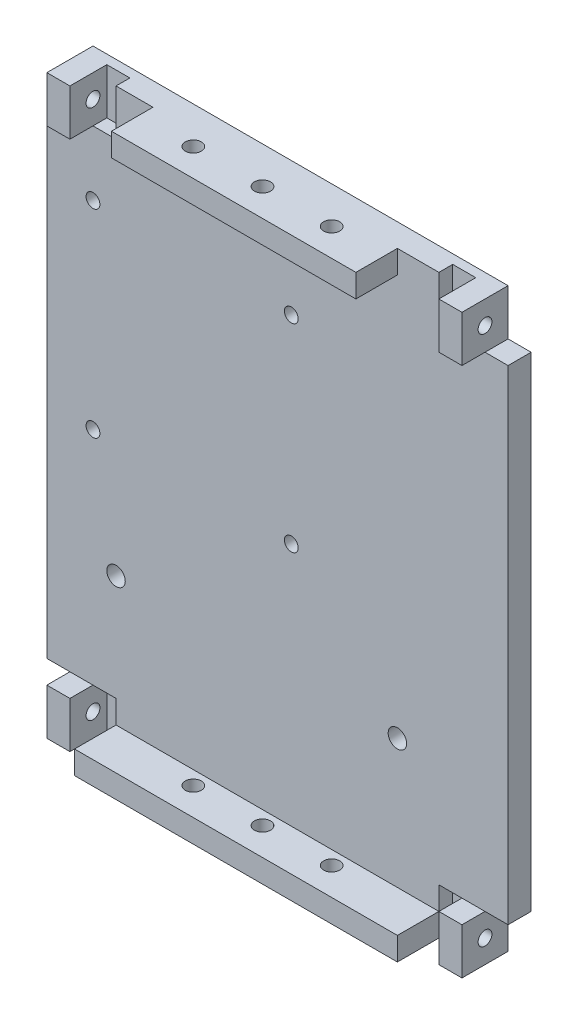
SolidWorks part; units mm, degrees
ref_plane "Front Plane" through (0, 0, 0) normal (0, 0, 1) x (1, 0, 0)
ref_plane "Top Plane" through (0, 0, 0) normal (0, 1, 0) x (1, 0, 0)
ref_plane "Right Plane" through (0, 0, 0) normal (1, 0, 0) x (0, 0, -1)
sketch "Sketch1" plane through (0, 0, 0) normal (0, 0, 1) x (1, 0, 0)
  line L1 (-95, 125) -> (-5, 125)
  line L2 (-95, 125) -> (-95, 0)
  line L3 (-95, 0) -> (-5, 0)
  line L4 (-5, 125) -> (-5, 0)
extrude "Boss-Extrude1" add sketch "Sketch1" along normal blind 5
sketch "Sketch2" plane through (-95, 0, 0) normal (-1, 0, 0) x (0, 0, 1)
  line L0 (10, 115) -> (0, 115) construction
  line L1 (5, 115) -> (0, 115)
  line L2 (5, 115) -> (5, 10)
  line L3 (5, 10) -> (0, 10)
  line L4 (0, 115) -> (0, 10)
  line L5 (0, 125) -> (0, 0) construction
  line L6 (10, 10) -> (0, 10) construction
extrude "Boss-Extrude2" add sketch "Sketch2" along normal up to surface (5 mm away)
sketch "Sketch3" plane through (0, 0, 5) normal (0, 0, 1) x (1, 0, 0)
  line L1 (-5, 125) -> (-10, 125)
  line L2 (-5, 125) -> (-5, 115)
  line L3 (-5, 115) -> (-10, 115)
  line L4 (-10, 125) -> (-10, 115)
  line L5 (-95, 125) -> (-90, 125)
  line L6 (-95, 125) -> (-95, 115)
  line L7 (-95, 115) -> (-90, 115)
  line L8 (-90, 125) -> (-90, 115)
  line L9 (-5, 0) -> (-10, 0)
  line L10 (-5, 0) -> (-5, 10)
  line L11 (-5, 10) -> (-10, 10)
  line L12 (-10, 0) -> (-10, 10)
  line L13 (-95, 0) -> (-90, 0)
  line L14 (-95, 0) -> (-95, 10)
  line L15 (-95, 10) -> (-90, 10)
  line L16 (-90, 0) -> (-90, 10)
  dimension "D1" = 5
  dimension "D2" = 10
extrude "Boss-Extrude3" add sketch "Sketch3" along normal up to surface (5 mm away)
sketch "Sketch4" plane through (0, 0, 5) normal (0, 0, 1) x (1, 0, 0)
  line L0 (-90, 0) -> (-10, 0) construction
  line L1 (-90, 125) -> (-85, 125)
  line L2 (-90, 125) -> (-90, 115)
  line L3 (-90, 115) -> (-85, 115)
  line L4 (-85, 125) -> (-85, 115)
  line L5 (-10, 125) -> (-15, 125)
  line L6 (-10, 125) -> (-10, 115)
  line L7 (-10, 115) -> (-15, 115)
  line L8 (-15, 125) -> (-15, 115)
  line L9 (-10, 0) -> (-15, 0)
  line L10 (-10, 0) -> (-10, 10)
  line L11 (-10, 10) -> (-15, 10)
  line L12 (-15, 0) -> (-15, 10)
  line L13 (-90, 0) -> (-85, 0)
  line L14 (-90, 0) -> (-90, 10)
  line L15 (-90, 10) -> (-85, 10)
  line L16 (-85, 0) -> (-85, 10)
  dimension "D1" = 5
  dimension "D2" = 10
extrude "Cut-Extrude1" cut sketch "Sketch4" against normal blind 3
sketch "Sketch5" plane through (0, 0, 0) normal (1, 0, 0) x (0, 0, -1)
  circle A0 centre (-5, 5) radius 1.5
  circle A1 centre (-5, 120) radius 1.5
extrude "Cut-Extrude2" cut sketch "Sketch5" against normal up to surface (15 mm away) up to face at (-15, 5, 3.5)
sketch "Sketch6" plane through (-100, 0, 0) normal (-1, 0, 0) x (0, 0, 1)
  circle A0 centre (5, 5) radius 1.5
  circle A1 centre (5, 120) radius 1.5
extrude "Cut-Extrude3" cut sketch "Sketch6" against normal up to surface (15 mm away) up to face at (-85, 120, 3.5)
sketch "Sketch7" plane through (0, 0, 5) normal (0, 0, 1) x (1, 0, 0)
  line L0 (-15, 125) -> (-85, 125) construction
  line L1 (-77, 125) -> (-24, 125)
  line L2 (-77, 125) -> (-77, 120)
  line L3 (-77, 120) -> (-24, 120)
  line L4 (-24, 125) -> (-24, 120)
  line L5 (-85, 0) -> (-85, 10) construction
  line L6 (-85, 0) -> (-15, 0)
  line L7 (-85, 0) -> (-85, 5)
  line L8 (-85, 5) -> (-15, 5)
  line L9 (-15, 0) -> (-15, 5)
  line L10 (-15, 10) -> (-15, 0) construction
  line L11 (-85, 0) -> (-15, 0) construction
  dimension "D1" = 0
  dimension "D2" = 5
  dimension "D3" = 5
extrude "Boss-Extrude4" add sketch "Sketch7" along normal up to surface (9 mm away)
sketch "Sketch8" plane through (0, 0, 0) normal (0, -1, 0) x (1, 0, 0)
  circle A0 centre (-65.25, 8) radius 1.75
  circle A1 centre (-50.25, 8) radius 1.75
  circle A2 centre (-35.25, 8) radius 1.75
extrude "Cut-Extrude4" cut sketch "Sketch8" against normal up to surface (125 mm away) up to face at (-49.5937, 125, 6.25)
sketch "Sketch9" plane through (0, 0, 5) normal (0, 0, 1) x (1, 0, 0)
  line L0 (-100, 115) -> (-100, 10) construction
  line L1 (-77, 125) -> (-85, 125) construction
  circle A0 centre (-47, 101) radius 1.5
  circle A1 centre (-90, 101) radius 1.5
  circle A2 centre (-90, 58) radius 1.5
  circle A3 centre (-47, 58) radius 1.5
  dimension "D1" = 3
  dimension "D4" = 10
  dimension "D5" = 24
  dimension "D2" = 43
  dimension "D3" = 43
extrude "Cut-Extrude5" cut sketch "Sketch9" against normal up to surface (5 mm away) up to face at (-74.375, 63.75, 0)
sketch "Sketch10" plane through (0, 0, 5) normal (0, 0, 1) x (1, 0, 0)
  line L2 (-100, 115) -> (-100, 10) construction
  circle A0 centre (-85, 33) radius 2
  circle A1 centre (-24, 33) radius 2
  circle A2 centre (-90, 58) radius 1.5 construction
  dimension "D1" = 4
  dimension "D2" = 25
  dimension "D4" = 15
  dimension "D3" = 61
extrude "Cut-Extrude6" cut sketch "Sketch10" against normal up to surface (5 mm away) up to face at (-45.5, 58, 0)
sketch "Sketch11" plane through (-5, 0, 0) normal (1, 0, 0) x (0, 0, -1)
  line L0 (0, 0) -> (0, 125) construction
  line L1 (-5, 115) -> (0, 115)
  line L2 (-5, 115) -> (-5, 10)
  line L3 (-5, 10) -> (0, 10)
  line L4 (0, 115) -> (0, 10)
extrude "Boss-Extrude5" add sketch "Sketch11" along normal blind 5
